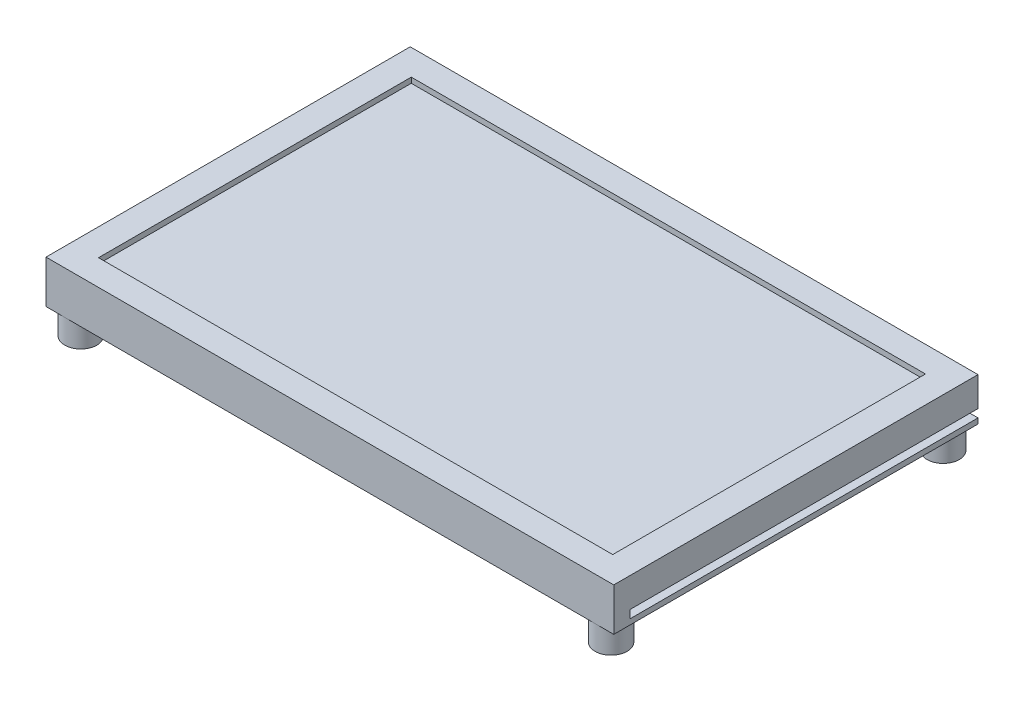
SolidWorks part; units mm, degrees
ref_plane "Plan de face" through (0, 0, 0) normal (0, 0, 1) x (1, 0, 0)
ref_plane "Plan de dessus" through (0, 0, 0) normal (0, 1, 0) x (1, 0, 0)
ref_plane "Plan de droite" through (0, 0, 0) normal (1, 0, 0) x (0, 0, -1)
sketch "Esquisse1" plane through (0, 0, 0) normal (0, 1, 0) x (1, 0, 0)
  line L1 (-53, 34) -> (53, 34)
  line L2 (-53, 34) -> (-53, -34)
  line L3 (-53, -34) -> (53, -34)
  line L4 (53, 34) -> (53, -34)
  line L5 (-53, 34) -> (53, -34) construction
  line L6 (-53, -34) -> (53, 34) construction
  point P0 (0, 0)
  dimension "D1" = 106
  dimension "D2" = 68
extrude "Boss.-Extru.1" add sketch "Esquisse1" along normal blind 8
sketch "Esquisse2" plane through (0, 0, 0) normal (0, -1, 0) x (1, 0, 0)
  line L0 (-53, 34) -> (53, 34) construction
  line L2 (-53, -34) -> (-53, 34) construction
  line L3 (0, 0) -> (0, 50000) construction
  line L4 (0, 0) -> (50000, 0) construction
  circle A0 centre (-49.5, 31) radius 3
  circle A1 centre (-49.5, -31) radius 3
  circle A2 centre (49.5, -31) radius 3
  circle A3 centre (49.5, 31) radius 3
  circle A5 centre (-30.5, 24.5) radius 3
  circle A6 centre (27.5, 24.5) radius 3
  circle A10 centre (27.5, -24.5) radius 3
  circle A11 centre (-30.5, -24.5) radius 3
  dimension "D1" = 6
  dimension "D2" = 3.5
  dimension "D3" = 58
  dimension "D4" = 49
  dimension "D6" = 49
  dimension "D5" = 19
extrude "Boss.-Extru.2" add sketch "Esquisse2" along normal blind 4.5
sketch "Esquisse3" plane through (0, -4.5, 0) normal (0, -1, 0) x (1, 0, 0)
  line L0 (0, 0) -> (0, 50000) construction
  line L1 (0, 0) -> (-50000, 0) construction
  line L2 (-30.5, 24.5) -> (27.5, 24.5) construction
  line L3 (27.5, 24.5) -> (27.5, -24.5) construction
  circle A0 centre (-49.5, 31) radius 1.25
  circle A1 centre (49.5, 31) radius 1.25
  circle A2 centre (49.5, -31) radius 1.25
  circle A3 centre (-49.5, -31) radius 1.25
  circle A4 centre (-30.5, 24.5) radius 1.25
  circle A5 centre (27.5, 24.5) radius 1.25
  circle A6 centre (27.5, -24.5) radius 1.25
  circle A7 centre (-30.5, -24.5) radius 1.25
  dimension "D1" = 2.5
extrude "Enlèv. mat.-Extru.1" cut sketch "Esquisse3" against normal blind 7
sketch "Esquisse4" plane through (0, 0, -34) normal (0, 0, -1) x (-1, 0, 0)
  line L7 (-53, 8) -> (-53, 0) construction
  line L8 (-53, 1) -> (53, 1)
  line L9 (-53, 1) -> (-53, 2.5)
  line L10 (-53, 2.5) -> (53, 2.5)
  line L11 (53, 1) -> (53, 2.5)
  line L12 (53, 8) -> (53, 0) construction
  line L13 (-49.5, 0) -> (49.5, 0) construction
  dimension "D1" = 1
  dimension "D2" = 1.5
extrude "Enlèv. mat.-Extru.3" cut sketch "Esquisse4" against normal blind 65
sketch "Esquisse10" plane through (0, 8, 0) normal (0, 1, 0) x (1, 0, 0)
  line L1 (-48, 29.1952) -> (48, 29.1952)
  line L2 (-48, 29.1952) -> (-48, -29.1952)
  line L3 (-48, -29.1952) -> (48, -29.1952)
  line L4 (48, 29.1952) -> (48, -29.1952)
  line L5 (-48, 29.1952) -> (48, -29.1952) construction
  line L6 (-48, -29.1952) -> (48, 29.1952) construction
  line L7 (53, -34) -> (53, 34) construction
  point P0 (0, 0)
  dimension "D1" = 5
extrude "Enlèv. mat.-Extru.5" cut sketch "Esquisse10" against normal blind 1
equation "\"D2@Esquisse2\"=\"D1@Esquisse2\" / 2 + 0.5"
